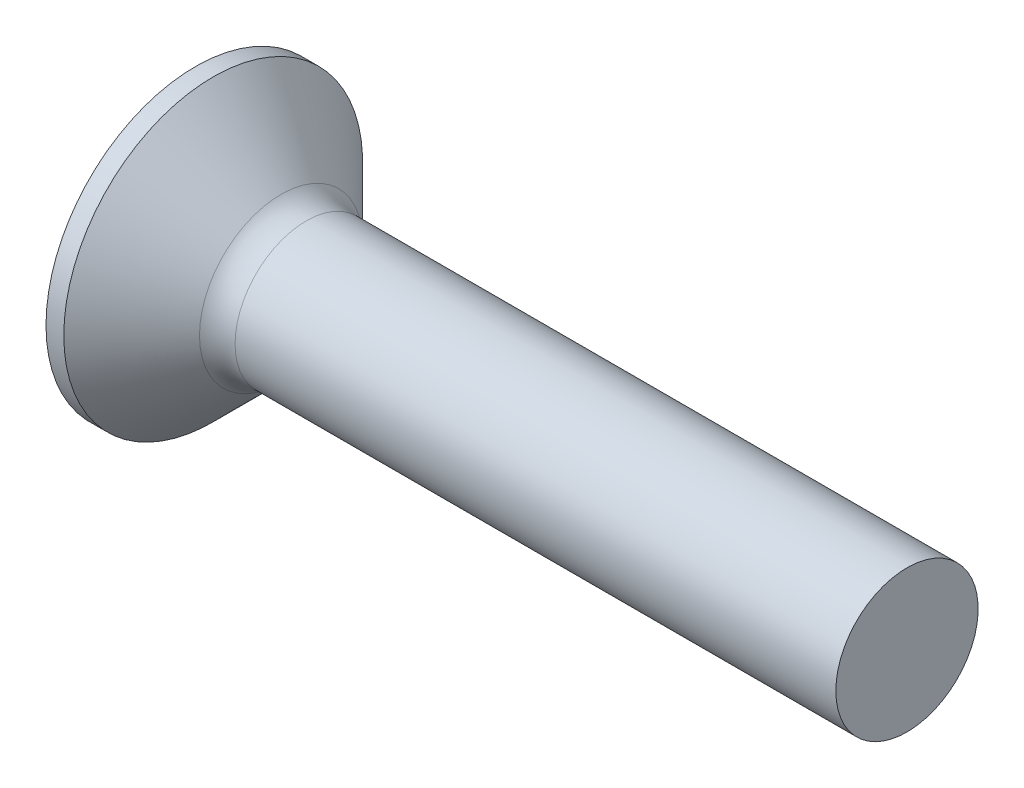
SolidWorks part; units mm, degrees
revolve "Base-Revolve" add sketch "BodySke"
sketch "BodySke" plane through (0, 0, 0) normal (0, 0, 1) x (1, 0, 0)
  line L0 (0, 0) -> (0, 4.2)
  line L1 (0, 4.2) -> (0.5, 4.2)
  line L2 (2.7, 2) -> (20, 2)
  line L3 (20, 2) -> (20, 0)
  line L4 (20, 0) -> (0, 0)
  line L5 (-6.35, 0) -> (82.55, 0) construction
  line L6 (2.7, -2) -> (20, -2) construction
  line L7 (0.5, -4.2) -> (2.7, -2) construction
  line L8 (0.5, 4.2) -> (2.7, 2)
  line L9 (0, -4.2) -> (0.5, -4.2) construction
  line L10 (3.4, 3.5875) -> (3.4, -5.9375) construction
  line L11 (0, 6.35) -> (0, -3.175) construction
  dimension "Head_ang" = 90
cosmetic thread "ThreadCosmetic"
fillet "Fillet1" radius 1 1 edges at (2.7, 0, 2)
ref_plane "Plane1" through (0, 0, 0) normal (0, 0, 1) x (1, 0, 0)
ref_plane "Plane2" through (0, 0, 0) normal (0, 1, 0) x (1, 0, 0)
ref_plane "Plane3" through (0, 0, 0) normal (1, 0, 0) x (0, 0, -1)
other "Configuration Table"
sketch "Sketch3" plane through (0, 0, 0) normal (-1, 0, 0) x (0, 0, 1)
  line L0 (-0.515, 2.2) -> (0.515, 2.2)
  line L1 (0.515, 2.2) -> (0.515, -2.2)
  line L2 (0.515, -2.2) -> (-0.515, -2.2)
  line L3 (-0.515, -2.2) -> (-0.515, 2.2)
  dimension "D1" = 0.95
  dimension "D2" = 0.24
ref_plane "Plane4" through (2.51, 0, 0) normal (-1, 0, 0) x (0, 0, 1)
sketch "Sketch4" plane through (2.51, 0, 0) normal (-1, 0, 0) x (0, 0, 1)
  line L0 (-0.515, 0.9486) -> (0.515, 0.9486)
  line L3 (0.515, 0.9486) -> (0.515, -0.9486)
  line L4 (0.515, -0.9486) -> (-0.515, -0.9486)
  line L5 (-0.515, -0.9486) -> (-0.515, 0.9486)
  dimension "D2" = 0.7034
  dimension "D1" = 0.48
  dimension "D4" = 0.3517
  dimension "D3" = 0.24
loft "Recess" cut profiles "Sketch3", "Sketch4"
pattern_circular "RecPat" count 2 every 90 about axis through (0, 0, 0) along (1, 0, 0) of "Recess"
sketch "RecCorSke" plane through (0, 0, 0) normal (0, 0, 1) x (1, 0, 0)
  line L0 (-3.175, 0) -> (15.875, 0) construction
  line L2 (0, 0) -> (0, 1.0265)
  line L3 (0, 1.0265) -> (2.51, 0.851)
  line L4 (2.51, 0.851) -> (2.7865, 0)
  line L5 (2.7865, 0) -> (0, 0)
  dimension "Depth" = 1.2
  dimension "Draft_angle" = 4
  dimension "Bottom_angle" = 18
revolve "RecessCore" cut sketch "RecCorSke" angle 360 about L0
sketch "ThdSchSke" plane through (0, 0, 0) normal (0, 0, 1) x (1, 0, 0)
  line L0 (3.4, -1.61) -> (3.1269, -2)
  line L1 (3.4, -1.61) -> (3.6731, -2)
  line L2 (3.6731, -2) -> (3.6731, -2.5)
  line L3 (-3.175, 0) -> (5.1513, 0) construction
  line L5 (3.6731, -2.5) -> (3.1269, -2.5)
  line L6 (3.1269, -2.5) -> (3.1269, -2)
  line L7 (0, 4.2) -> (0, -4.2) construction
  dimension "Thread_minor" = 1.548
  dimension "Diameter" = 2
  dimension "Start" = 1.6
revolve "ThreadSchematic" [suppressed] cut sketch "ThdSchSke" angle 360 about L3
pattern_linear "ThdSchPat" [suppressed]
equation "\"D1@Sketch3\" = \"Cross_dia@Sketch3\" / 2"
equation "\"D2@Sketch3\" = \"Cross_width@Sketch3\" / 2"
equation "\"Depth@RecCorSke\" = \"Cross_depth@Plane4\""
equation "\"D1@Sketch4\" = \"Cross_width@Sketch3\""
equation "\"D2@Sketch4\" = \"Cross_dia@Sketch3\" - 2.0 * \"Cross_depth@Plane4\" * tan(26.5  * 0.017453292)"
equation "\"D3@Sketch4\" = \"D1@Sketch4\" / 2"
equation "\"D4@Sketch4\" = \"D2@Sketch4\" / 2"
equation "\"Thread_length@ThreadCosmetic\" = ((sgn( (\"Length@BodySke\" - \"Advance@BodySke\" * 1.0 - \"Head_ht@BodySke\" ) - \"Thread_nom@BodySke\" )-1)*( (\"Length@BodySke\" - \"Advance@BodySke\" * 1.0 - \"Head_ht@BodySke\" ) - \"Thread_nom@BodySke\" ))/-2+ \"Thread_nom@BodySke\""
equation "\"Thread_minor@ThdSchSke\" = \"Thread_minor@ThreadCosmetic\""
equation "\"Diameter@ThdSchSke\" = \"Diameter@BodySke\""
equation "\"Overcut@ThdSchSke\" = \"Diameter@BodySke\" * 1.25"
equation "\"Start@ThdSchSke\" = 0.000001 + \"Length@BodySke\" - \"Thread_length@ThreadCosmetic\"  '---Countersunk---"
equation "\"Num_threads@ThdSchPat\" = int( \"Thread_length@ThreadCosmetic\" / \"Advance@BodySke\" + 0.999 )  + 1"
equation "\"Advance@ThdSchPat\" = \"Thread_length@ThreadCosmetic\" /  (\"Num_threads@ThdSchPat\" - 1) 'relax it"
